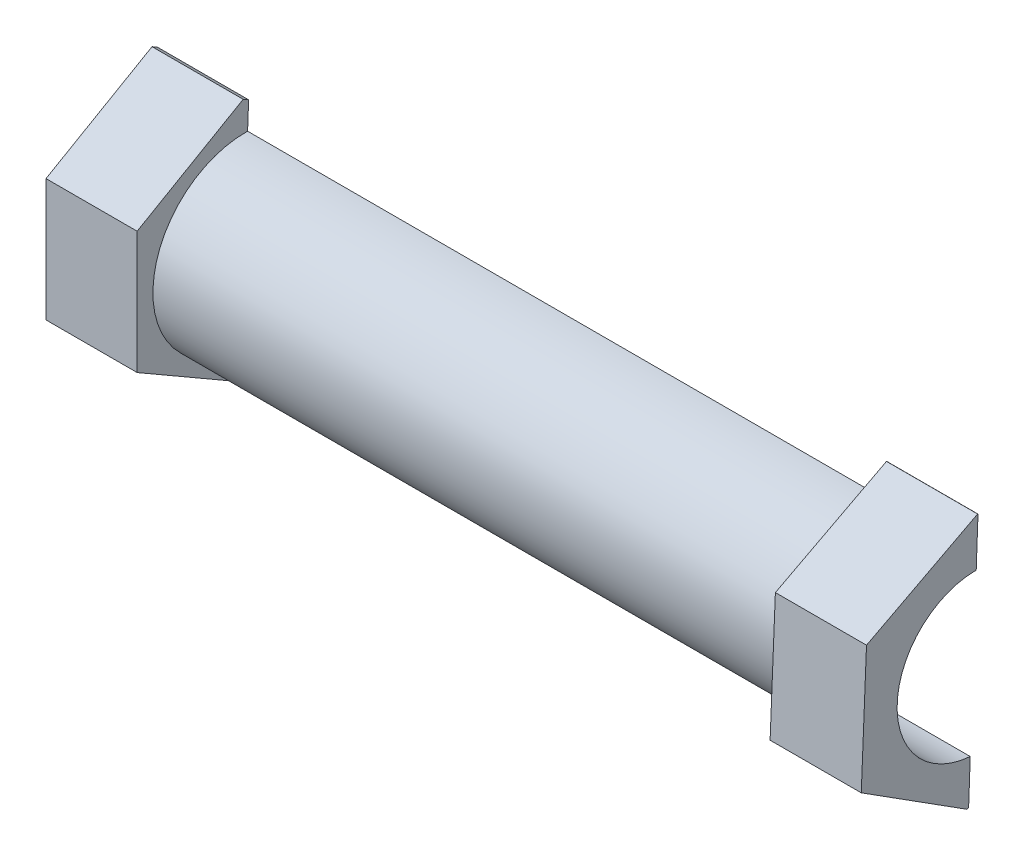
SolidWorks part; units mm, degrees
ref_plane "Front Plane" through (0, 0, 0) normal (0, 0, 1) x (1, 0, 0)
ref_plane "Top Plane" through (0, 0, 0) normal (0, 1, 0) x (1, 0, 0)
ref_plane "Right Plane" through (0, 0, 0) normal (1, 0, 0) x (0, 0, -1)
sketch "Sketch1" plane through (0, 0, 0) normal (1, 0, 0) x (0, 0, -1)
  circle A0 centre (1.2897, 0) radius 50.8004
  circle A1 centre (1.2897, 0) radius 47.813
extrude "Boss-Extrude2" add sketch "Sketch1" along normal blind 350
sketch "Sketch3" plane through (350, 0, 0) normal (1, 0, 0) x (0, 0, -1)
  line L1 (29.4119, -18.9904) -> (30.3159, 11.3837)
  line L2 (30.3159, 11.3837) -> (4.4631, 27.3538)
  line L3 (4.4631, 27.3538) -> (-22.2937, 12.9496)
  line L4 (-22.2937, 12.9496) -> (-23.1978, -17.4246)
  line L5 (-23.1978, -17.4246) -> (2.655, -33.3946)
  line L6 (2.655, -33.3946) -> (29.4119, -18.9904)
  line L7 (58.0556, -36.8554) -> (60.9455, 31.8499)
  line L8 (60.9455, 31.8499) -> (2.8899, 68.7054)
  line L9 (2.8899, 68.7054) -> (-58.0556, 36.8554)
  line L10 (-58.0556, 36.8554) -> (-60.9455, -31.8499)
  line L11 (-60.9455, -31.8499) -> (-2.8899, -68.7054)
  line L12 (-2.8899, -68.7054) -> (58.0556, -36.8554)
  circle A0 centre (3.5591, -3.0204) radius 26.3165 construction
  circle A1 centre (0, 0) radius 59.5532 construction
  point P9 (-38.2851, 22.8279)
extrude "Boss-Extrude5" add sketch "Sketch3" along normal blind 50
sketch "Sketch5" plane through (0, 0, 0) normal (-1, 0, 0) x (0, 0, 1)
  line L1 (0, -67.1614) -> (58.1634, -33.5807)
  line L2 (58.1634, -33.5807) -> (58.1634, 33.5807)
  line L3 (58.1634, 33.5807) -> (0, 67.1614)
  line L4 (0, 67.1614) -> (-58.1634, 33.5807)
  line L5 (-58.1634, 33.5807) -> (-58.1634, -33.5807)
  line L6 (-58.1634, -33.5807) -> (0, -67.1614)
  circle A0 centre (0, 0) radius 58.1634 construction
extrude "Boss-Extrude11" add sketch "Sketch5" along normal blind 50
sketch "Sketch6" plane through (0, 0, 0) normal (1, 0, 0) x (0, 0, -1)
  circle A0 centre (2.1673, 0) radius 44.9963
  point P2 (2.0814, 2.5081)
  point P3 (2.1673, 0)
extrude "Cut-Extrude2" cut sketch "Sketch6" against normal blind 50
sketch "Sketch7" plane through (350, 0, 0) normal (-1, 0, 0) x (0, 0, 1)
  circle A0 centre (-2.2315, -1.0944) radius 43.5179
  point P2 (-2.2315, -1.0944)
extrude "Cut-Extrude3" cut sketch "Sketch7" against normal blind 50
sketch "Sketch9" plane through (400, 0, 0) normal (1, 0, 0) x (0, 0, -1)
  line L1 (3.4354, 77.5085) -> (88.3726, 77.5085)
  line L2 (3.4354, 77.5085) -> (-2.6728, -84.9391)
  line L3 (-2.6728, -84.9391) -> (88.3726, -82.2739)
  line L4 (88.3726, 77.5085) -> (88.3726, -82.2739)
  point P4 (-1.9103, -82.2739)
  point P5 (-2.6728, -84.9391)
extrude "Cut-Extrude5" cut sketch "Sketch9" against normal through all
